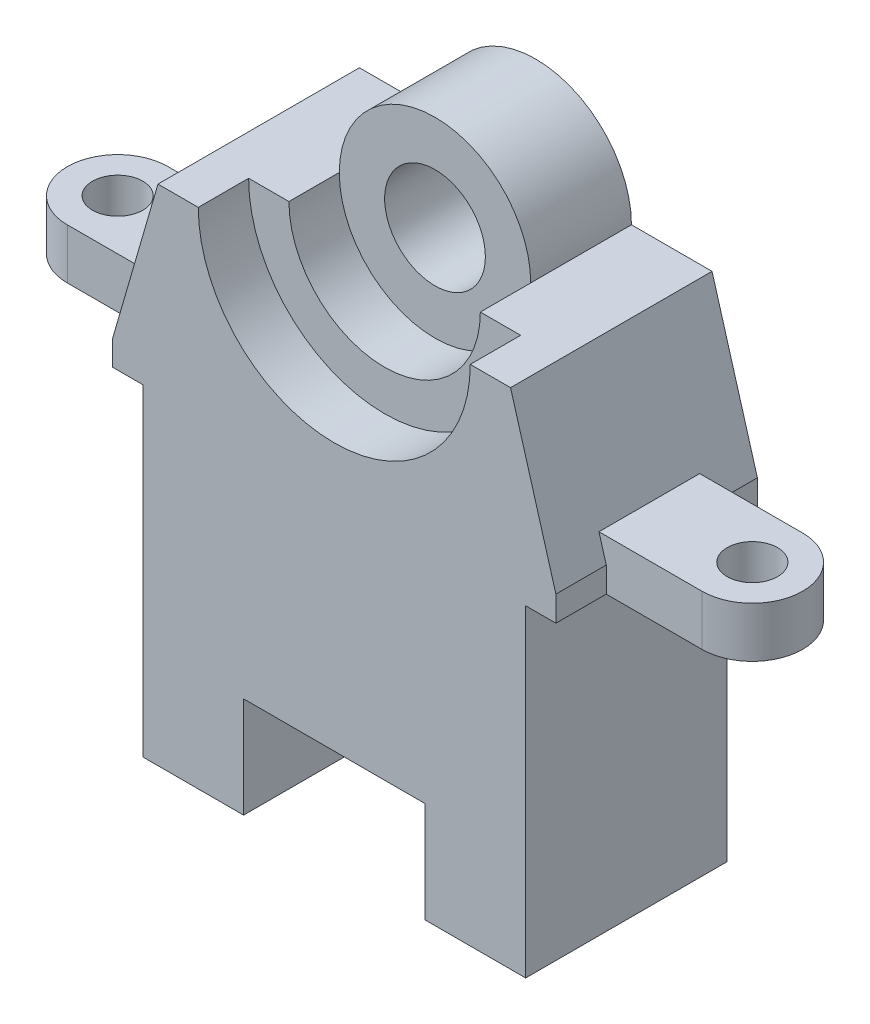
SolidWorks part; units mm, degrees
ref_plane "Front Plane" through (0, 0, 0) normal (0, 0, 1) x (1, 0, 0)
ref_plane "Top Plane" through (0, 0, 0) normal (0, 1, 0) x (1, 0, 0)
ref_plane "Right Plane" through (0, 0, 0) normal (1, 0, 0) x (0, 0, -1)
sketch "Sketch1" plane through (0, 0, 0) normal (0, 0, 1) x (1, 0, 0)
  line L0 (0, 0) -> (0, 64)
  line L1 (0, 0) -> (20, 0)
  line L2 (20, 0) -> (20, 20)
  line L3 (20, 20) -> (56, 20)
  line L4 (56, 20) -> (56, 0)
  line L5 (56, 0) -> (76, 0)
  line L6 (76, 0) -> (76, 64)
  line L7 (0, 64) -> (-6, 64)
  line L8 (-6, 64) -> (-6, 69)
  line L9 (73, 100) -> (3, 100)
  line L11 (3, 100) -> (-6, 69)
  line L12 (82, 64) -> (82, 69)
  line L13 (76, 64) -> (82, 64)
  line L14 (73, 100) -> (82, 69)
  dimension "D1" = 3
  dimension "D2" = 20
  dimension "D3" = 56
  dimension "D4" = 82
  dimension "D5" = 64
  dimension "D6" = 69
  dimension "D7" = 100
extrude "Boss-Extrude1" add sketch "Sketch1" along normal blind 40
sketch "Sketch2" plane through (0, 0, 40) normal (0, 0, 1) x (1, 0, 0)
  line L0 (73, 100) -> (3, 100) construction
  circle A2 centre (38, 100) radius 27
  dimension "D1" = 54
extrude "Cut-Extrude3" cut sketch "Sketch2" against normal blind 10
sketch "Sketch4" plane through (0, 0, 30) normal (0, 0, 1) x (1, 0, 0)
  line L0 (65, 100) -> (11, 100) construction
  circle A0 centre (38, 100) radius 19
extrude "Cut-Extrude4" cut sketch "Sketch4" against normal blind 10
sketch "Sketch5" plane through (0, 0, 20) normal (0, 0, 1) x (1, 0, 0)
  line L0 (57, 100) -> (19, 100) construction
  circle A0 centre (38, 100) radius 19
extrude "Boss-Extrude2" add sketch "Sketch5" against normal blind 20
sketch "Sketch6" plane through (0, 0, 20) normal (0, 0, 1) x (1, 0, 0)
  circle A0 centre (38, 100) radius 10
extrude "Cut-Extrude6" cut sketch "Sketch6" against normal blind 20
sketch "Sketch7" plane through (0, 0, 0) normal (0, 1, 0) x (1, 0, 0)
  line L0 (82, -10) -> (77.668, -10)
  line L1 (-6, -10) -> (-2.3899, -10)
  line L2 (-25, -10) -> (-6, -10)
  line L3 (-6, -40) -> (-6, 0) construction
  line L4 (-25, -30) -> (-6, -30)
  line L5 (-2.3899, -10) -> (-2.3899, -30)
  line L6 (-2.3899, -30) -> (-6, -30)
  line L7 (101, -30) -> (82, -30)
  line L8 (101, -10) -> (82, -10)
  line L10 (77.668, -10) -> (77.668, -30)
  line L11 (77.668, -30) -> (82, -30)
  circle A0 centre (-25, -20) radius 5
  arc A1 (-25, -10) -> (-25, -30) centre (-25, -20) ccw
  arc A2 (101, -10) -> (101, -30) centre (101, -20) cw
  circle A3 centre (101, -20) radius 5
  dimension "D1" = 10
  dimension "D2" = 10
  dimension "D3" = 77.668
  dimension "D4" = 82
  dimension "D5" = 101
  dimension "D6" = 2.3899
  dimension "D7" = 20
extrude "Boss-Extrude4" add sketch "Sketch7" along normal blind 10 from offset 64
